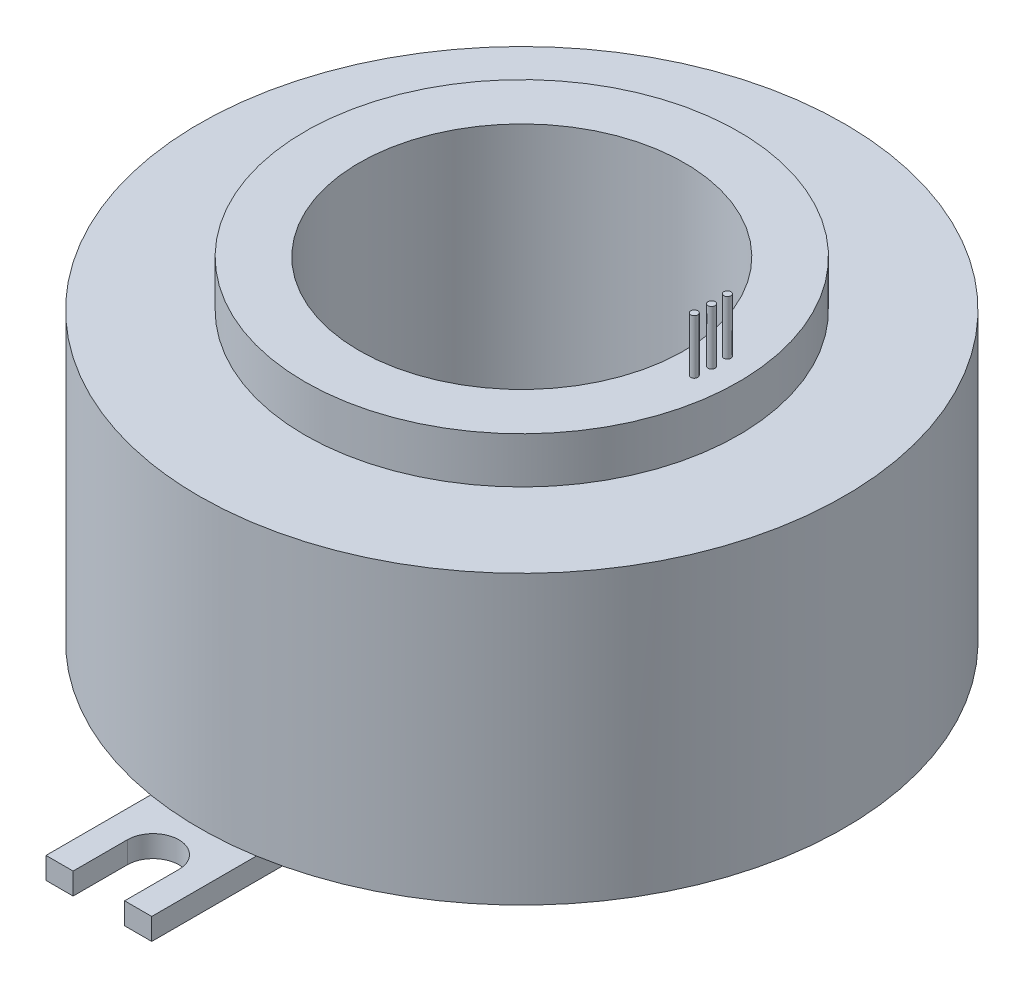
SolidWorks part; units mm, degrees
ref_plane "Alzado" through (0, 0, 0) normal (0, 0, 1) x (1, 0, 0)
ref_plane "Planta" through (0, 0, 0) normal (0, 1, 0) x (1, 0, 0)
ref_plane "Vista lateral" through (0, 0, 0) normal (1, 0, 0) x (0, 0, -1)
sketch "Croquis1" plane through (0, 0, 0) normal (0, 1, 0) x (1, 0, 0)
  circle A0 centre (0, 0) radius 59.5
  dimension "D1" = 119
extrude "Saliente-Extruir1" add sketch "Croquis1" along normal blind 53
sketch "Croquis2" plane through (0, 53, 0) normal (0, 1, 0) x (1, 0, 0)
  circle A0 centre (0, 0) radius 40
  dimension "D1" = 80
extrude "Saliente-Extruir2" add sketch "Croquis2" along normal blind 8.5
sketch "Croquis4" plane through (0, 61.5, 0) normal (0, 1, 0) x (1, 0, 0)
  circle A0 centre (0, 0) radius 30
  dimension "D1" = 60
extrude "Cortar-Extruir1" cut sketch "Croquis4" against normal up to next
sketch "Croquis5" plane through (0, 61.5, 0) normal (0, 1, 0) x (1, 0, 0)
  line L0 (0, 0) -> (35, 0) construction
  line L1 (0, 0) -> (34.8668, 3.0505) construction
  circle A0 centre (0, 0) radius 35 construction
  circle A1 centre (35, 0) radius 0.65
  circle A2 centre (34.8668, 3.0505) radius 0.65
  circle A4 centre (34.8668, -3.0505) radius 0.65
  dimension "D1" = 70
  dimension "D2" = 5
  dimension "D4" = 1.3
  dimension "D5" = 1.3
extrude "Saliente-Extruir3" add sketch "Croquis5" along normal blind 10
sketch "Croquis6" plane through (0, 0, 0) normal (0, -1, 0) x (1, 0, 0)
  line L0 (0, 0) -> (45, 0) construction
  line L1 (0, 0) -> (44.8288, 3.922) construction
  circle A0 centre (0, 0) radius 45 construction
  circle A1 centre (45, 0) radius 0.65
  circle A2 centre (44.8288, 3.922) radius 0.65
  circle A3 centre (44.8288, -3.922) radius 0.65
  dimension "D1" = 90
  dimension "D2" = 5
  dimension "D3" = 1.3
  dimension "D4" = 1.3
extrude "Saliente-Extruir4" add sketch "Croquis6" along normal blind 10
sketch "Croquis10" plane through (0, 0, 0) normal (0, -1, 0) x (1, 0, 0)
  line L0 (0, 0) -> (0, 48) construction
  line L1 (-4.75, 68) -> (-4.75, 78)
  line L2 (0, 59.5) -> (0, 78) construction
  line L3 (-9.75, 78) -> (9.75, 78)
  line L6 (4.75, 68) -> (4.75, 78)
  line L7 (-9.75, 78) -> (-9.75, 48)
  line L8 (-9.75, 48) -> (9.75, 48)
  line L9 (9.75, 48) -> (9.75, 78)
  line L10 (-9.75, 48) -> (9.75, 48)
  circle A0 centre (0, 0) radius 59.5 construction
  arc A2 (-4.75, 68) -> (4.75, 68) centre (0, 68) ccw
  point P7 (0, 68)
  point P9 (0, 59.5)
  point P13 (0, 78)
  circle M12 centre (0, 0) radius 59.5
  dimension "D3" = 9.5
  dimension "D1" = 30
  dimension "D2" = 18.5
  dimension "D4" = 10
extrude "Saliente-Extruir5" add sketch "Croquis10" along normal blind 4 contours A2 L1 L3 L7 L9 L6 M12 | L8 L9 L7 M12
